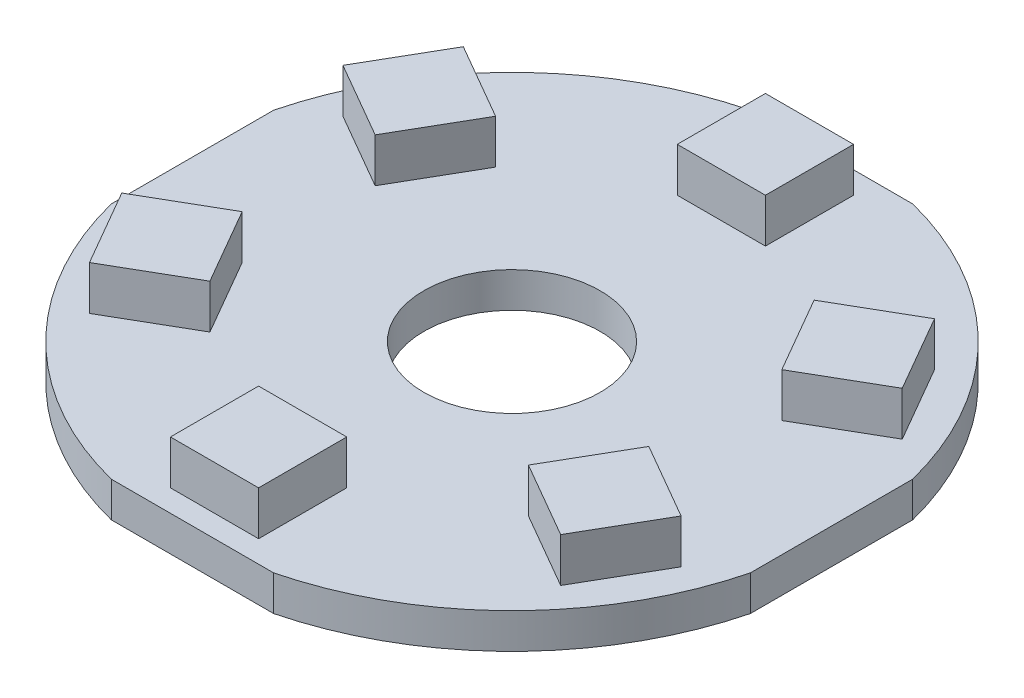
SolidWorks part; units mm, degrees
ref_plane "Front Plane" through (0, 0, 0) normal (0, 0, 1) x (1, 0, 0)
ref_plane "Top Plane" through (0, 0, 0) normal (0, 1, 0) x (1, 0, 0)
ref_plane "Right Plane" through (0, 0, 0) normal (1, 0, 0) x (0, 0, -1)
sketch "Sketch1" plane through (0, 0, 0) normal (0, 1, 0) x (1, 0, 0)
  circle A0 centre (0, 0) radius 19
  circle A1 centre (0, 0) radius 5.08
  dimension "D1" = 38
  dimension "D2" = 10.16
extrude "Boss-Extrude1" add sketch "Sketch1" along normal blind 2.032
sketch "Sketch2" plane through (0, 2.032, 0) normal (0, 1, 0) x (1, 0, 0)
  line L0 (0, 0) -> (0, 19) construction
  line L1 (-4.6784, 18.415) -> (4.6784, 18.415)
  line L2 (0, 0) -> (19, 0) construction
  line L3 (-4.6784, -18.415) -> (4.6784, -18.415)
  circle A1 centre (0, 0) radius 19
  arc A2 (-4.6784, -18.415) -> (4.6784, -18.415) centre (0, 0) ccw
  arc A3 (4.6784, 18.415) -> (-4.6784, 18.415) centre (0, 0) ccw
  point P7 (0, 18.415)
  dimension "D3" = 36.83
  dimension "D1" = 0
extrude "Cut-Extrude1" cut sketch "Sketch2" against normal through all
pattern_circular "CirPattern1" count 2 every 90 about axis through (0, 2.032, 0) along (0, -1, 0) of "Cut-Extrude1"
sketch "Sketch3" plane through (0, 2.032, 0) normal (0, 1, 0) x (1, 0, 0)
  line L0 (0, 0) -> (0, 50000) construction
  line L1 (0, 0) -> (50000, 0) construction
  line L2 (-4.6784, 18.415) -> (4.6784, 18.415) construction
  line L3 (-2.54, 17.145) -> (2.54, 17.145)
  line L4 (-2.54, 17.145) -> (-2.54, 12.065)
  line L5 (-2.54, 12.065) -> (2.54, 12.065)
  line L6 (2.54, 17.145) -> (2.54, 12.065)
  line L7 (-2.54, 17.145) -> (2.54, 12.065) construction
  line L8 (-2.54, 12.065) -> (2.54, 17.145) construction
  point P6 (0, 14.605)
  dimension "D1" = 5.08
  dimension "D2" = 5.08
  dimension "D3" = 1.27
extrude "Boss-Extrude2" add sketch "Sketch3" along normal blind 2.54
pattern_circular "CirPattern2" count 6 every 60 about axis through (0, 0, 0) along (0, 1, 0) of "Boss-Extrude2"
